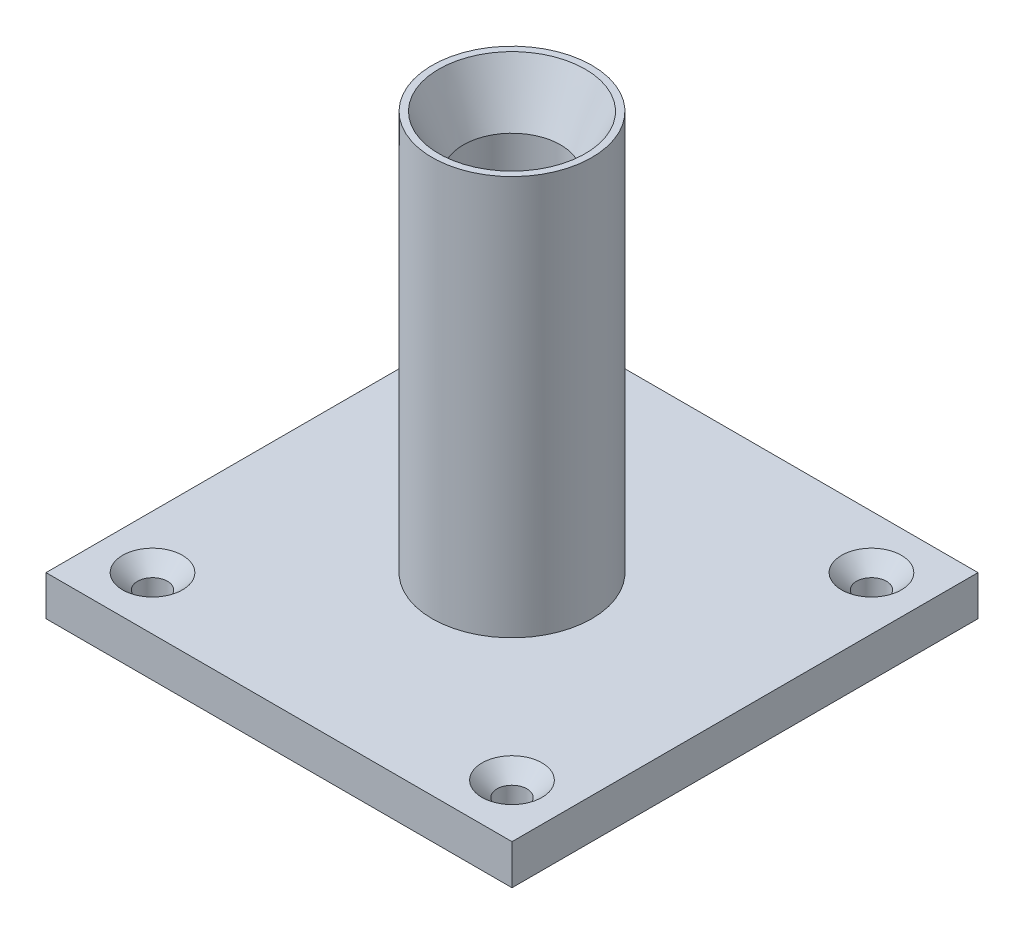
SolidWorks part; units mm, degrees
ref_plane "Alzado" through (0, 0, 0) normal (0, 0, 1) x (1, 0, 0)
ref_plane "Planta" through (0, 0, 0) normal (0, 1, 0) x (1, 0, 0)
ref_plane "Vista lateral" through (0, 0, 0) normal (1, 0, 0) x (0, 0, -1)
sketch "Croquis1" plane through (0, 0, 0) normal (0, 1, 0) x (1, 0, 0)
  line L0 (-35, -35) -> (35, -35)
  line L1 (35, -35) -> (35, 35)
  line L2 (35, 35) -> (-35, 35)
  line L3 (-35, 35) -> (-35, -35)
sketch "Croquis2" plane through (0, 0, 0) normal (0, 0, 1) x (1, 0, 0)
  line L0 (7.3, 6) -> (12, 6)
  line L1 (12, 6) -> (12, 66)
  line L2 (12, 66) -> (11, 66)
  line L3 (11, 66) -> (7.3, 58)
  line L4 (7.3, 58) -> (7.3, 6)
  line L5 (0, 0) -> (0, 70) construction
extrude "Saliente-Extruir1" add sketch "Croquis1" along normal blind 6
revolve "Revolución1" add sketch "Croquis2" angle 360 about L5
ref_plane "Plano fondo" through (0, 6, 0) normal (0, 1, 0) x (1, 0, 0)
sketch "Croquis3" plane through (0, 6, 0) normal (0, 1, 0) x (1, 0, 0)
  line L0 (6.3, -3.6878) -> (6.3, 3.6878)
  arc A0 (6.3, -3.6878) -> (6.3, 3.6878) centre (0, 0) ccw
sketch "Croquis4" plane through (0, 0, 0) normal (0, 1, 0) x (1, 0, 0)
  circle A0 centre (27, 27) radius 2.25
  circle A1 centre (27, -27) radius 2.25
  circle A2 centre (-27, 27) radius 2.25
  circle A3 centre (-27, -27) radius 2.25
extrude "Saliente-Extruir2" add sketch "Croquis3" along normal blind 52
extrude "Cortar-Extruir1" cut sketch "Croquis4" along normal through all
chamfer "Chaflán1" distance 2.25 angle 45 4 edges at (27, 6, -24.75) (-27, 6, 29.25) (-27, 6, -24.75) (27, 6, 29.25)
